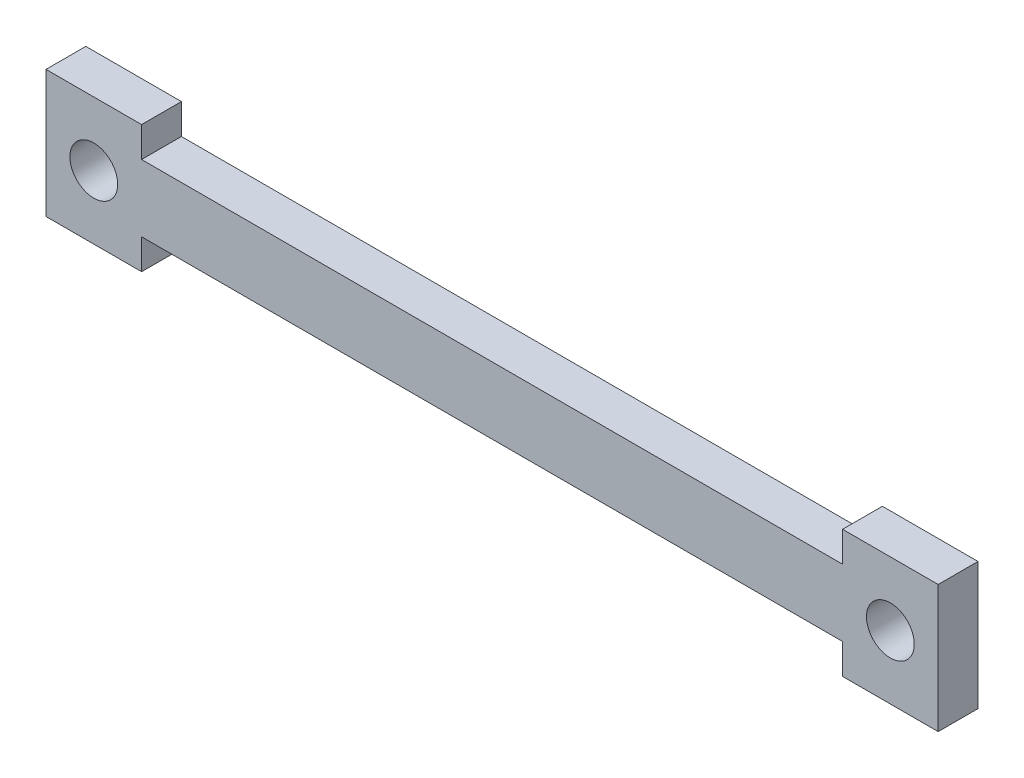
SolidWorks part; units mm, degrees
ref_plane "Спереди" through (0, 0, 0) normal (0, 0, 1) x (1, 0, 0)
ref_plane "Сверху" through (0, 0, 0) normal (0, 1, 0) x (1, 0, 0)
ref_plane "Справа" through (0, 0, 0) normal (1, 0, 0) x (0, 0, -1)
sketch "Эскиз1" plane through (0, 0, 0) normal (0, 0, 1) x (1, 0, 0)
  line L0 (-28, -0.914) -> (-22, -0.914) construction
  line L1 (-28, 4) -> (-22, 4)
  line L2 (-28, 4) -> (-28, -4)
  line L3 (-28, -4) -> (-22, -4)
  line L4 (28, 4) -> (28, -4)
  line L5 (-28, 4) -> (28, -4) construction
  line L6 (-28, -4) -> (28, 4) construction
  line L7 (28, 0) -> (22, 0) construction
  line L8 (-22, 4) -> (-22, 2.1)
  line L9 (-22, 2.1) -> (22, 2.1)
  line L11 (-22, -2.1) -> (22, -2.1)
  line L13 (-22, 2.1) -> (22, -2.1) construction
  line L14 (-22, -2.1) -> (22, 2.1) construction
  line L15 (-22, -2.1) -> (-22, -4)
  line L16 (22, -2.1) -> (22, -4)
  line L17 (22, 4) -> (22, 2.1)
  line L18 (22, 4) -> (28, 4)
  line L19 (22, -4) -> (28, -4)
  point P0 (0, 0)
  point P10 (0, 0)
  dimension "D1" = 56
  dimension "D2" = 8
  dimension "D3" = 6
  dimension "D4" = 6
  dimension "D5" = 4.2
extrude "Бобышка-Вытянуть1" add sketch "Эскиз1" along normal blind 2.5
sketch "Эскиз2" plane through (0, 0, 2.5) normal (0, 0, 1) x (1, 0, 0)
  line L0 (-25, 4) -> (-25, -4) construction
  line L1 (-22, 4) -> (-28, 4) construction
  line L2 (-28, -4) -> (-22, -4) construction
  line L3 (-25, -4) -> (-28, -4) construction
  line L4 (-28, -4) -> (-25, 0) construction
  line L5 (0, 0) -> (0, -1.5305) construction
  circle A0 centre (-25, 0) radius 1.5
  circle A1 centre (25, 0) radius 1.5
  dimension "D1" = 3
extrude "Вырез-Вытянуть1" cut sketch "Эскиз2" against normal blind 2.5
